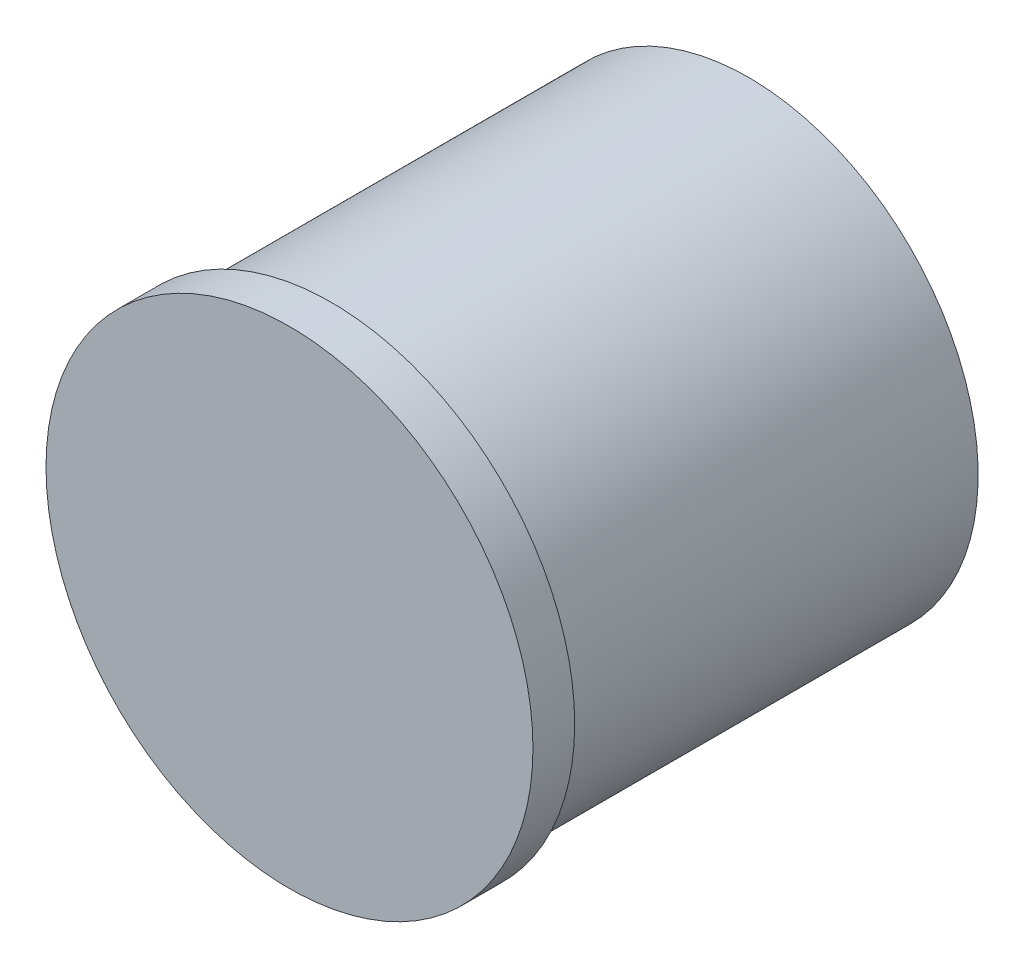
SolidWorks part; units mm, degrees
material "PVC Rigid"
ref_plane "Front Plane" through (0, 0, 0) normal (0, 0, 1) x (1, 0, 0)
ref_plane "Top Plane" through (0, 0, 0) normal (0, 1, 0) x (1, 0, 0)
ref_plane "Right Plane" through (0, 0, 0) normal (1, 0, 0) x (0, 0, -1)
sketch "Sketch1" plane through (0, 0, 0) normal (0, 1, 0) x (1, 0, 0)
  line L0 (0, 0) -> (13.5, 0) construction
  line L1 (13.5, 15) -> (13.5, -15)
  line L2 (13.5, 15) -> (16.5, 15)
  line L3 (16.5, 15) -> (16.5, -15)
  line L4 (16.5, -15) -> (13.5, -15)
  line L5 (0, -15) -> (0, -12)
  line L6 (0, -12) -> (13.5, -12)
  line L7 (0, -15) -> (13.5, -15)
  line L8 (0, 0) -> (0, -9.7101) construction
  point P6 (13.5, 0)
  dimension "D1" = 13.5
  dimension "D2" = 3
  dimension "D3" = 3
  dimension "D4" = 30
revolve "Revolve1" add sketch "Sketch1" angle 360 about L8
sketch "Sketch2" plane through (0, 0, 15) normal (0, 0, 1) x (1, 0, 0)
  circle A0 centre (0, 0) radius 17.5
  dimension "D1" = 35
extrude "Boss-Extrude1" add sketch "Sketch2" along normal blind 3
